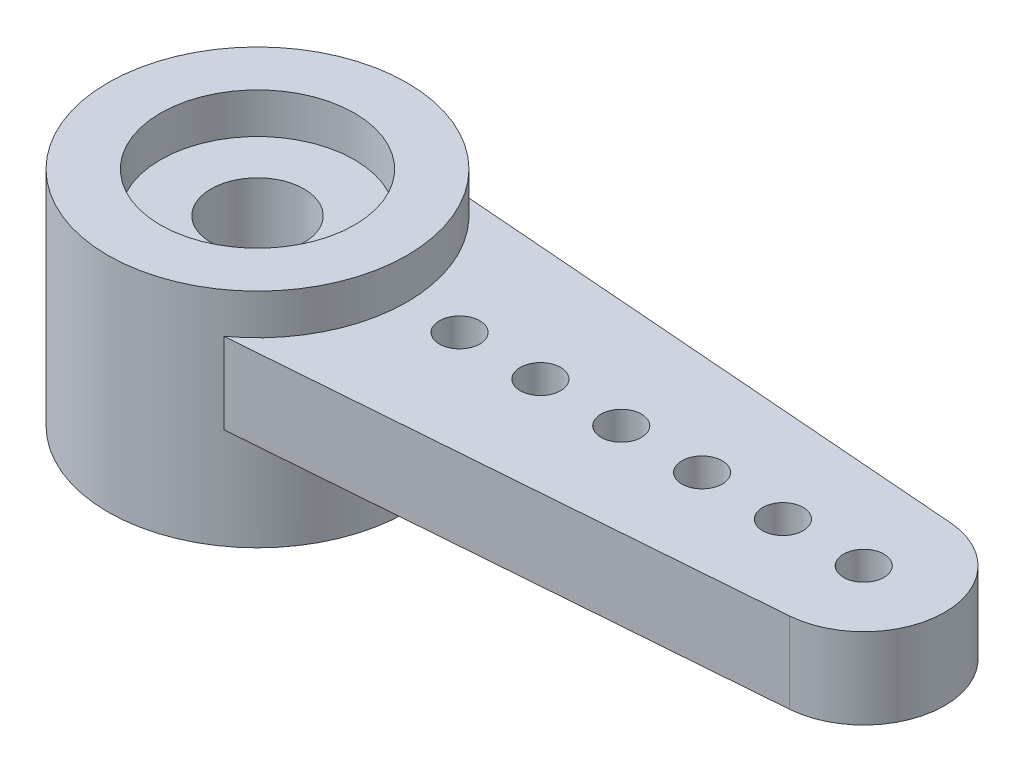
SolidWorks part; units mm, degrees
ref_plane "Plan de face" through (0, 0, 0) normal (0, 0, 1) x (1, 0, 0)
ref_plane "Plan de dessus" through (0, 0, 0) normal (0, 1, 0) x (1, 0, 0)
ref_plane "Plan de droite" through (0, 0, 0) normal (1, 0, 0) x (0, 0, -1)
sketch "Esquisse1" plane through (0, 0, 0) normal (0, 0, 1) x (1, 0, 0)
  line L0 (0, 0) -> (0, 10.9842) construction
  line L1 (-2.4, 0) -> (-2.4, 3)
  line L2 (-2.4, 3) -> (-1.15, 3)
  line L3 (-1.15, 3) -> (-1.15, 4.5)
  line L4 (-1.15, 4.5) -> (-2.4, 4.5)
  line L5 (-2.4, 4.5) -> (-2.4, 5.5)
  line L6 (-2.4, 5.5) -> (-3.7, 5.5)
  line L7 (-3.7, 5.5) -> (-3.7, 0)
  line L8 (-3.7, 0) -> (-2.4, 0)
  dimension "D1" = 7.4
  dimension "D2" = 5.5
  dimension "D3" = 4.8
  dimension "D4" = 1
  dimension "D5" = 2.3
  dimension "D6" = 1.5
revolve "Révolution1" add sketch "Esquisse1" angle 360 about L0
sketch "Esquisse2" plane through (0, 5.5, 0) normal (0, 1, 0) x (1, 0, 0)
  line L0 (0, 0) -> (15, 0) construction
  line L1 (2.1656, 3) -> (15.1544, 1.994)
  line L2 (15.1544, -1.994) -> (2.1656, -3)
  circle A0 centre (0, 0) radius 3.7 construction
  arc A1 (15.1544, 1.994) -> (15.1544, -1.994) centre (15, 0) cw
  arc A2 (2.1656, -3) -> (2.1656, 3) centre (0, 0) ccw
  circle A3 centre (15, 0) radius 0.5
  circle A4 centre (13, 0) radius 0.5
  circle A5 centre (11, 0) radius 0.5
  circle A6 centre (9, 0) radius 0.5
  circle A7 centre (7, 0) radius 0.5
  circle A8 centre (5, 0) radius 0.5
  dimension "D2" = 1
  dimension "D3" = 2
  dimension "D6" = 2
  dimension "D1" = 15
  dimension "D4" = 6
  dimension "D5" = 6
extrude "Boss.-Extru.1" add sketch "Esquisse2" against normal blind 2 from offset 1 offset against normal yes
